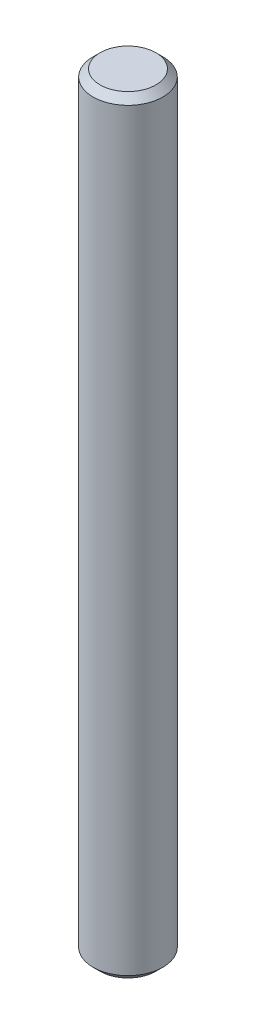
SolidWorks part; units mm, degrees
ref_plane "Ön Düzlem" through (0, 0, 0) normal (0, 0, 1) x (1, 0, 0)
ref_plane "Üst Düzlem" through (0, 0, 0) normal (0, 1, 0) x (1, 0, 0)
ref_plane "Sağ Düzlem" through (0, 0, 0) normal (1, 0, 0) x (0, 0, -1)
sketch "Çizim1" plane through (0, 0, 0) normal (0, 1, 0) x (1, 0, 0)
  circle A0 centre (0, 0) radius 0.5
  dimension "D1" = 1
extrude "Yükseklik-Ekstrüzyon1" add sketch "Çizim1" along normal mid plane 10
chamfer "Pah1" distance 0.1 angle 45 2 edges at (0, -5, 0.5) (0, 5, 0.5)
sketch "Çizim2" plane through (0, 5, 0) normal (0, 1, 0) x (1, 0, 0)
  circle A0 centre (0, 0) radius 0.5 construction
  circle A1 centre (0, 0) radius 0.5
extrude "Yükseklik-Ekstrüzyon2" add sketch "Çizim2" along normal blind 1 and the other way blind 1
chamfer "Pah2" distance 0.1 angle 45 1 edges at (0, 6, 0.5)
